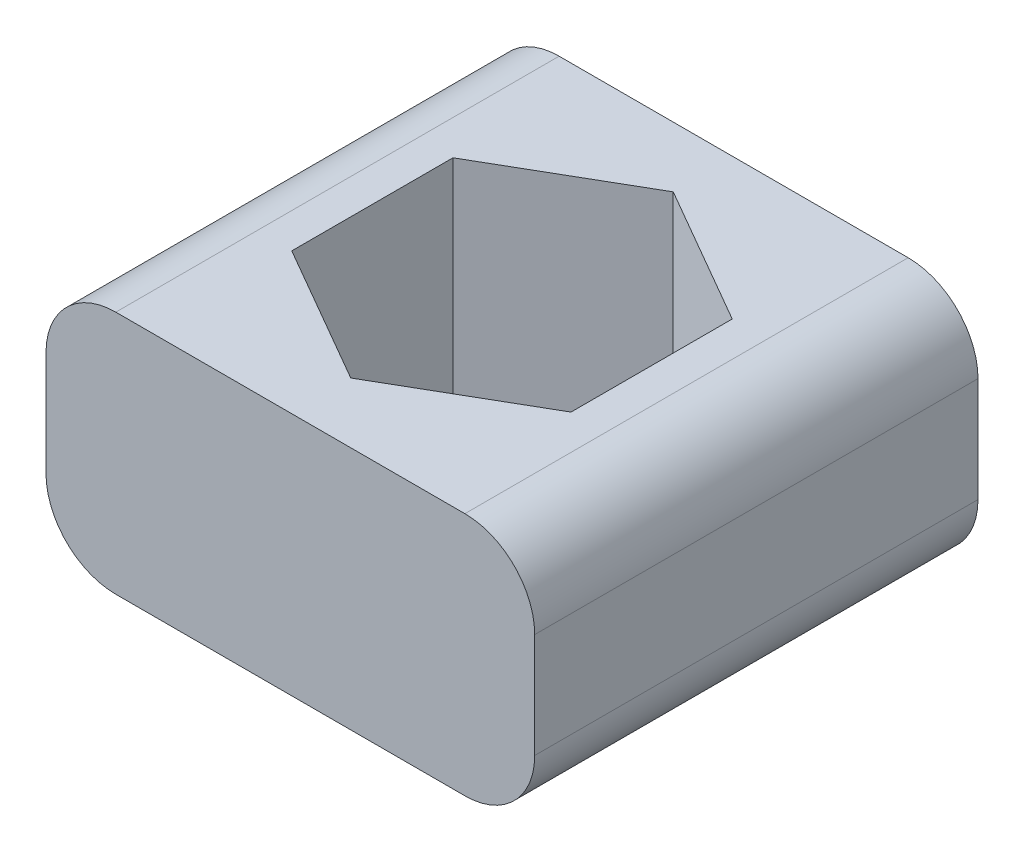
SolidWorks part; units mm, degrees
material "ABS"
ref_plane "Front Plane" through (0, 0, 0) normal (0, 0, 1) x (1, 0, 0)
ref_plane "Top Plane" through (0, 0, 0) normal (0, 1, 0) x (1, 0, 0)
ref_plane "Right Plane" through (0, 0, 0) normal (1, 0, 0) x (0, 0, -1)
sketch "Sketch1" plane through (0, 0, 0) normal (0, 0, 1) x (1, 0, 0)
  line L0 (-7, 0) -> (7, 0)
  line L1 (-7, 0) -> (-7, -7)
  line L2 (-7, -7) -> (7, -7)
  line L3 (7, -7) -> (7, 0)
  dimension "D1" = 14
  dimension "D2" = 7
extrude "Boss-Extrude1" add sketch "Sketch1" along normal mid plane 12.7
sketch "Sketch2" plane through (0, 0, 0) normal (0, 1, 0) x (1, 0, 0)
  line L1 (0, -4.6188) -> (4, -2.3094)
  line L2 (4, -2.3094) -> (4, 2.3094)
  line L3 (4, 2.3094) -> (0, 4.6188)
  line L4 (0, 4.6188) -> (-4, 2.3094)
  line L5 (-4, 2.3094) -> (-4, -2.3094)
  line L6 (-4, -2.3094) -> (0, -4.6188)
  circle A0 centre (0, 0) radius 4 construction
  point P1 (0, 0)
  point P10 (0, 0)
  point P11 (0.1985, 4.6145)
  dimension "D1" = 8
extrude "Cut-Extrude1" cut sketch "Sketch2" against normal blind 6
fillet "Fillet1" radius 2 4 edges at (7, 0, 0) (7, -7, 0) (-7, -7, 0) (-7, 0, 0)
hole_wizard "M5 Clearance Hole1" positions "Sketch3" profile "Sketch4" hole size "M5" standard "ANSI Metric" end condition through all
sketch "Sketch3" plane through (0, -7, 0) normal (0, -1, 0) x (-1, 0, 0)
  point P0 (0, 0)
sketch "Sketch4" plane through (0, -7, 0) normal (1, 0, 0) x (0, 0, -1)
  line L0 (0, 0) -> (0, 7)
  line L1 (0, 7) -> (2.65, 7)
  line L2 (2.65, 7) -> (2.65, 0)
  line L5 (2.65, 0) -> (0, 0)
  line L11 (0, -6.35) -> (0, 107.95) construction
  dimension "Thru Hole Dia." = 5.3
  dimension "Thru Hole Depth" = 7
